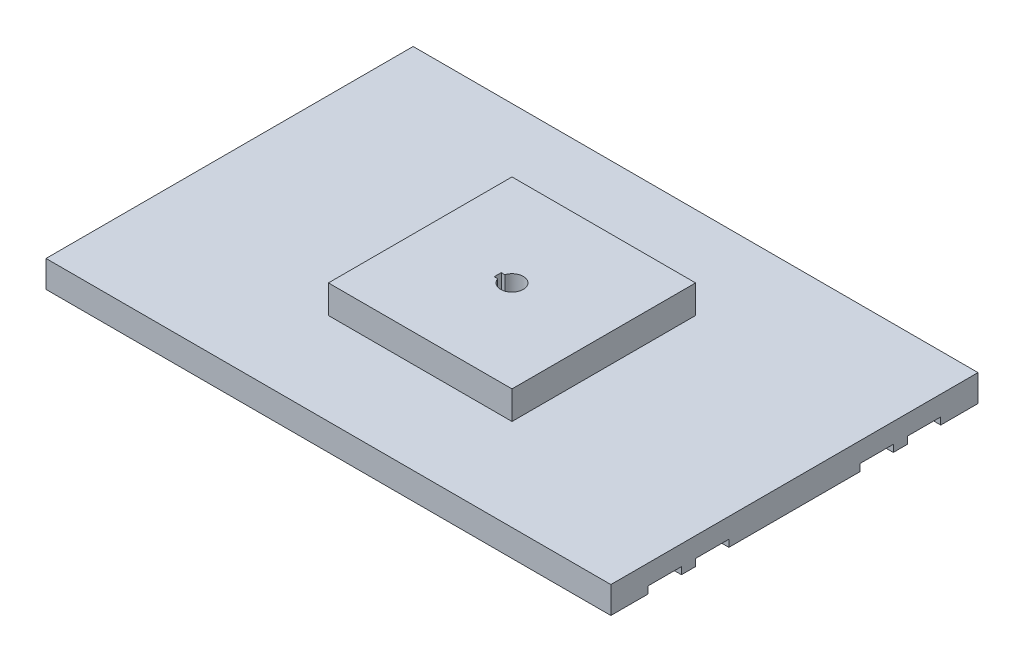
SolidWorks part; units mm, degrees
material "1060 Alloy"
ref_plane "Front Plane" through (0, 0, 0) normal (0, 0, 1) x (1, 0, 0)
ref_plane "Top Plane" through (0, 0, 0) normal (0, 1, 0) x (1, 0, 0)
ref_plane "Right Plane" through (0, 0, 0) normal (1, 0, 0) x (0, 0, -1)
sketch "Sketch1" plane through (0, 0, 0) normal (0, 1, 0) x (1, 0, 0)
  line L1 (-200, -130) -> (200, -130)
  line L2 (-200, -130) -> (-200, 130)
  line L3 (-200, 130) -> (200, 130)
  line L4 (200, -130) -> (200, 130)
  line L5 (-200, -130) -> (200, 130) construction
  line L6 (-200, 130) -> (200, -130) construction
  point P0 (0, 0)
  dimension "D1" = 400
  dimension "D2" = 260
extrude "Boss-Extrude1" add sketch "Sketch1" along normal blind 19
sketch "Sketch2" plane through (0, 0, 0) normal (0, -1, 0) x (1, 0, 0)
  line L0 (-200, 103.6) -> (200, 103.6)
  line L1 (200, 103.6) -> (200, 80)
  line L2 (200, 80) -> (-200, 80)
  line L3 (-200, 80) -> (-200, 103.6)
  line L4 (-200, 70) -> (200, 70)
  line L5 (200, 70) -> (200, 46.4)
  line L6 (200, 46.4) -> (-200, 46.4)
  line L7 (-200, 46.4) -> (-200, 70)
  line L8 (-200, 0) -> (214.3575, 0) construction
  line L9 (-200, -130) -> (-200, 130) construction
  line L10 (200, 130) -> (200, -130) construction
  line L11 (-200, 130) -> (200, 130) construction
  line L12 (-200, -46.4) -> (-200, -70)
  line L13 (200, -46.4) -> (-200, -46.4)
  line L14 (200, -70) -> (200, -46.4)
  line L15 (-200, -70) -> (200, -70)
  line L16 (-200, -80) -> (-200, -103.6)
  line L17 (200, -80) -> (-200, -80)
  line L18 (200, -103.6) -> (200, -80)
  line L19 (-200, -103.6) -> (200, -103.6)
  point P16 (-200, 58.2)
  dimension "D1" = 0
  dimension "D2" = 0
  dimension "D3" = 0
  dimension "D4" = 0
  dimension "D5" = 23.6
  dimension "D6" = 26.4
  dimension "D7" = 10
  dimension "D8" = 150
extrude "Cut-Extrude1" cut sketch "Sketch2" against normal blind 5
sketch "Sketch4" plane through (0, 19, 0) normal (0, 1, 0) x (1, 0, 0)
  line L1 (-65, 65) -> (65, 65)
  line L2 (-65, 65) -> (-65, -65)
  line L3 (-65, -65) -> (65, -65)
  line L4 (65, 65) -> (65, -65)
  line L5 (-65, 65) -> (65, -65) construction
  line L6 (-65, -65) -> (65, 65) construction
  point P0 (0, 0)
  dimension "D1" = 130
extrude "Boss-Extrude4" add sketch "Sketch4" along normal blind 20
sketch "Sketch5" plane through (0, 39, 0) normal (0, 1, 0) x (1, 0, 0)
  circle A0 centre (0, 0) radius 8
  dimension "D1" = 16
extrude "Cut-Extrude2" cut sketch "Sketch5" against normal through all
sketch "Sketch6" plane through (0, 39, 0) normal (0, 1, 0) x (1, 0, 0)
  line L0 (-10.0993, 2.5) -> (-10.0993, -2.5)
  line L1 (-10.0993, -2.5) -> (-7.5993, -2.5)
  line L2 (-10.0993, 2.5) -> (-7.5993, 2.5)
  line L3 (-7.5993, 2.5) -> (-7.5993, -2.5)
  circle A0 centre (0, 0) radius 8 construction
  dimension "D1" = 2.5
  dimension "D2" = 5
extrude "Cut-Extrude4" cut sketch "Sketch6" against normal through all
sketch "Sketch7" plane through (0, 0, 0) normal (0, -1, 0) x (1, 0, 0)
  circle A0 centre (0, 0) radius 25
  dimension "D1" = 50
extrude "Cut-Extrude5" cut sketch "Sketch7" against normal blind 19
